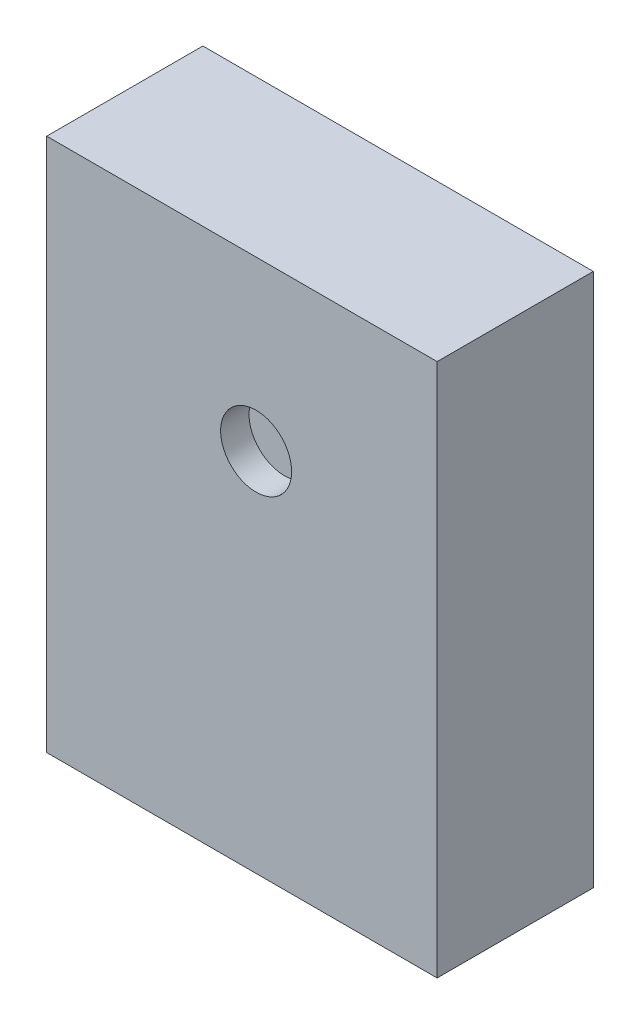
SolidWorks part; units mm, degrees
material "6063-T6"
ref_plane "Front Plane" through (0, 0, 0) normal (0, 0, 1) x (1, 0, 0)
ref_plane "Top Plane" through (0, 0, 0) normal (0, 1, 0) x (1, 0, 0)
ref_plane "Right Plane" through (0, 0, 0) normal (1, 0, 0) x (0, 0, -1)
sketch "Sketch1" plane through (0, 0, 0) normal (0, 0, 1) x (1, 0, 0)
  line L1 (-1.375, 1.88) -> (1.375, 1.88)
  line L2 (-1.375, 1.88) -> (-1.375, -1.88)
  line L3 (-1.375, -1.88) -> (1.375, -1.88)
  line L4 (1.375, 1.88) -> (1.375, -1.88)
  line L5 (-1.375, 1.88) -> (1.375, -1.88) construction
  line L6 (-1.375, -1.88) -> (1.375, 1.88) construction
  point P0 (0, 0)
  dimension "D1" = 3.76
  dimension "D2" = 2.75
extrude "Boss-Extrude1" add sketch "Sketch1" along normal blind 1.1
sketch "Sketch2" plane through (0, 0, 1.1) normal (0, 0, 1) x (1, 0, 0)
  line L1 (1.375, 1.88) -> (-1.375, 1.88) construction
  line L2 (-1.375, 1.88) -> (-1.375, -1.88) construction
  circle A0 centre (0.1, 0.696) radius 0.25
  dimension "D1" = 0.5
  dimension "D2" = 1.475
  dimension "D3" = 1.184
extrude "Cut-Extrude1" cut sketch "Sketch2" against normal blind 0.2
